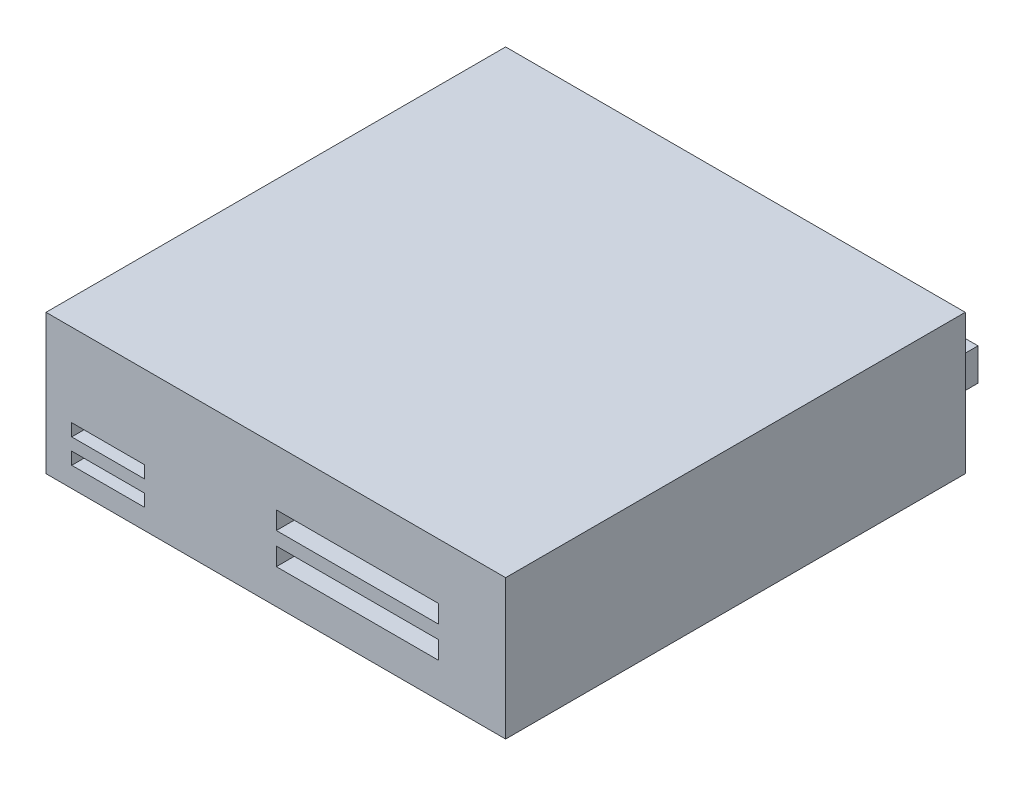
SolidWorks part; units mm, degrees
ref_plane "Front Plane" through (0, 0, 0) normal (0, 0, 1) x (1, 0, 0)
ref_plane "Top Plane" through (0, 0, 0) normal (0, 1, 0) x (1, 0, 0)
ref_plane "Right Plane" through (0, 0, 0) normal (1, 0, 0) x (0, 0, -1)
sketch "Sketch1" plane through (0, 0, 0) normal (0, 1, 0) x (1, 0, 0)
  line L1 (-20.55, -20.55) -> (20.55, -20.55)
  line L2 (-20.55, -20.55) -> (-20.55, 20.55)
  line L3 (-20.55, 20.55) -> (20.55, 20.55)
  line L4 (20.55, -20.55) -> (20.55, 20.55)
  line L5 (-20.55, -20.55) -> (20.55, 20.55) construction
  line L6 (-20.55, 20.55) -> (20.55, -20.55) construction
  point P0 (0, 0)
  dimension "D1" = 41.1
  dimension "D2" = 41.1
extrude "Boss-Extrude1" add sketch "Sketch1" along normal blind 12.5
sketch "Sketch2" plane through (0, 0, 20.55) normal (0, 0, 1) x (1, 0, 0)
  line L0 (-20.55, 12.5) -> (20.55, 12.5) construction
  line L1 (0.05, 7.5) -> (14.55, 7.5)
  line L2 (0.05, 7.5) -> (0.05, 5.9)
  line L3 (0.05, 5.9) -> (14.55, 5.9)
  line L4 (14.55, 7.5) -> (14.55, 5.9)
  line L5 (0.05, 4.7) -> (14.55, 4.7)
  line L6 (0.05, 4.7) -> (0.05, 3.1)
  line L7 (0.05, 3.1) -> (14.55, 3.1)
  line L8 (14.55, 4.7) -> (14.55, 3.1)
  line L9 (-18.25, 5.1) -> (-11.75, 5.1)
  line L10 (-18.25, 5.1) -> (-18.25, 4)
  line L11 (-18.25, 4) -> (-11.75, 4)
  line L12 (-11.75, 5.1) -> (-11.75, 4)
  line L13 (-18.25, 2.9) -> (-11.75, 2.9)
  line L14 (-18.25, 2.9) -> (-18.25, 1.8)
  line L15 (-18.25, 1.8) -> (-11.75, 1.8)
  line L16 (-11.75, 2.9) -> (-11.75, 1.8)
  line L17 (20.55, 12.5) -> (20.55, 0) construction
  line L18 (-20.55, 12.5) -> (-20.55, 0) construction
  line L19 (-20.55, 0) -> (20.55, 0) construction
  dimension "D1" = 14.5
  dimension "D2" = 1.6
  dimension "D3" = 1.2
  dimension "D4" = 5
  dimension "D5" = 6
  dimension "D6" = 1.1
  dimension "D7" = 1.1
  dimension "D8" = 1.1
  dimension "D9" = 2.3
  dimension "D10" = 1.8
  dimension "D11" = 6.5
extrude "Cut-Extrude1" cut sketch "Sketch2" against normal blind 30
sketch "Sketch3" plane through (0, 0, -20.55) normal (0, 0, -1) x (-1, 0, 0)
  line L1 (-18.6891, 7.4723) -> (-10.3199, 7.4723)
  line L2 (-18.6891, 7.4723) -> (-18.6891, 4.5777)
  line L3 (-18.6891, 4.5777) -> (-10.3199, 4.5777)
  line L4 (-10.3199, 7.4723) -> (-10.3199, 4.5777)
extrude "Boss-Extrude2" add sketch "Sketch3" along normal blind 3
